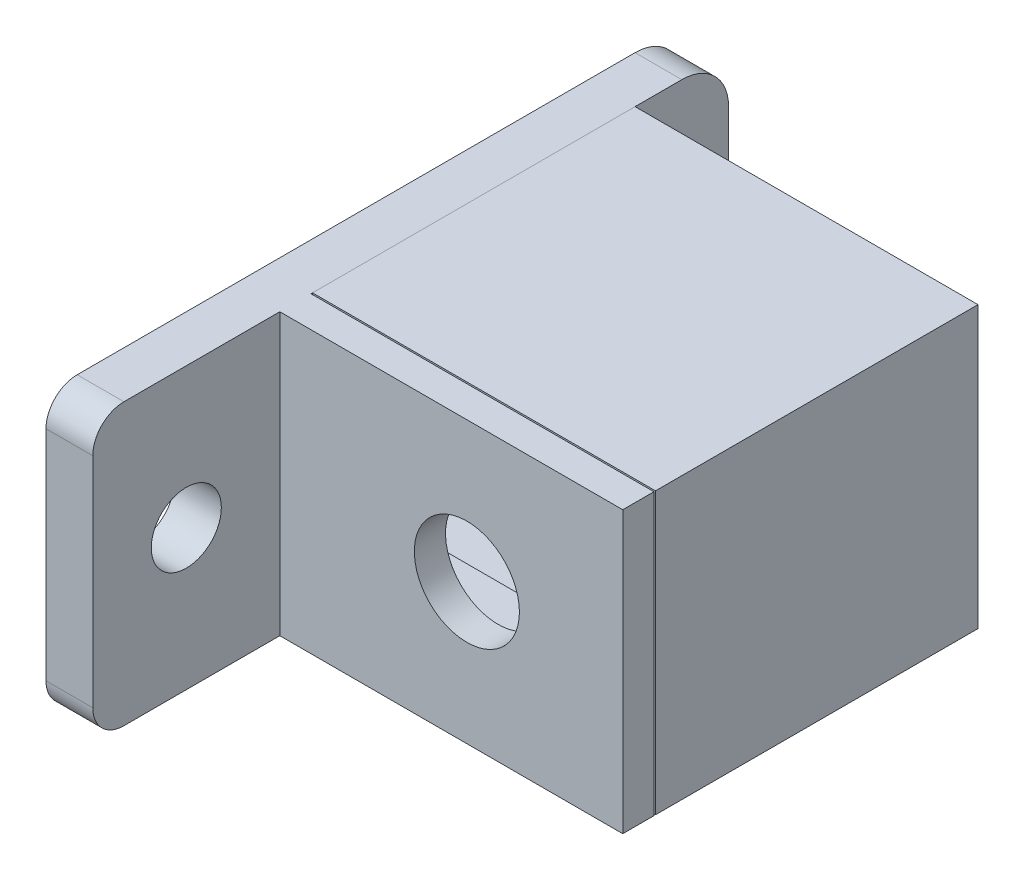
SolidWorks part; units mm, degrees
ref_plane "Front Plane" through (0, 0, 0) normal (0, 0, 1) x (1, 0, 0)
ref_plane "Top Plane" through (0, 0, 0) normal (0, 1, 0) x (1, 0, 0)
ref_plane "Right Plane" through (0, 0, 0) normal (1, 0, 0) x (0, 0, -1)
sketch "Sketch1" plane through (0, 0, 0) normal (1, 0, 0) x (0, 0, -1)
  line L1 (-13.46, 9) -> (-11.46, 9)
  line L2 (-13.46, 9) -> (-13.46, -9)
  line L3 (-13.46, -9) -> (-11.46, -9)
  line L4 (-11.46, 9) -> (-11.46, -9)
  line L5 (0, 0) -> (-11.46, 0) construction
  line L6 (-13.46, -6) -> (-13.46, 6) construction
  line L7 (-13.46, -6) -> (-13.46, 6) construction
  line L8 (4.33, 1.135) -> (4.33, -1.135) construction
  line L9 (4.33, 1.135) -> (4.33, -1.135) construction
  dimension "D1" = 3
  dimension "D2" = 2
extrude "Boss-Extrude1" add sketch "Sketch1" along normal blind 10 and the other way blind 15
sketch "Sketch2" plane through (0, 0, 11.46) normal (0, 0, -1) x (-1, 0, 0)
  line L0 (15, -9) -> (15, 9) construction
  line L1 (15, 9) -> (12, 9)
  line L2 (15, 9) -> (15, -9)
  line L3 (15, -9) -> (12, -9)
  line L4 (12, 9) -> (12, -9)
  line L5 (15, -9) -> (-10, -9) construction
  dimension "D1" = 3
extrude "Boss-Extrude2" add sketch "Sketch2" along normal offset from surface (20.79 mm away) 5
sketch "Sketch3" plane through (-12, 0, 0) normal (1, 0, 0) x (0, 0, -1)
  line L0 (-11.36, 9) -> (-11.36, 7)
  line L1 (-11.46, 9) -> (-11.46, -9) construction
  line L2 (-11.36, 7) -> (7.33, 7)
  line L3 (7.33, 7) -> (7.33, -7)
  line L4 (9.33, -9) -> (9.33, 9)
  line L5 (9.33, 9) -> (-11.46, 9)
  line L6 (-11.46, 9) -> (-11.46, -9)
  line L7 (-11.46, -9) -> (9.33, -9)
  line L8 (9.33, -9) -> (9.33, 9)
  line L9 (9.33, 9) -> (-11.36, 9)
  line L11 (-11.36, -9) -> (9.33, -9)
  line L12 (7.33, -7) -> (-11.36, -7)
  line L13 (-11.36, -7) -> (-11.36, -9)
  line L14 (7.33, 7) -> (9.33, 7) construction
  dimension "D2" = 0.1
  dimension "D3" = 2
  dimension "D1" = 0
extrude "Boss-Extrude3" add sketch "Sketch3" along normal up to surface (22 mm away) separate body up to face at (10, 0, 12.46)
sketch "Sketch4" plane through (-12, 0, 0) normal (1, 0, 0) x (0, 0, -1)
  line L0 (-11.46, 6.5) -> (-9.46, 6.5)
  line L1 (-11.46, -9) -> (-11.46, 9) construction
  line L2 (-9.46, 6.5) -> (-7.96, 8)
  line L3 (-7.96, 8) -> (-7.96, 4.5)
  line L4 (-7.96, 4.5) -> (-11.46, 4.5)
  line L5 (-11.46, 4.5) -> (-11.46, 6.5)
  line L6 (-11.46, 9) -> (-13.46, 9) construction
  line L7 (0, 0) -> (-5.1966, 0) construction
  line L8 (-7.96, -4.5) -> (-11.46, -4.5)
  line L9 (-7.96, -8) -> (-7.96, -4.5)
  line L10 (-9.46, -6.5) -> (-7.96, -8)
  line L11 (-11.46, -6.5) -> (-9.46, -6.5)
  line L12 (-11.46, -4.5) -> (-11.46, -6.5)
  dimension "D1" = 2
  dimension "D2" = 1.5
  dimension "D3" = 3.5
  dimension "D4" = 45
  dimension "D5" = 1
sketch "Sketch5" plane through (-12, 0, 0) normal (1, 0, 0) x (0, 0, -1)
  line L0 (-9.1014, 7) -> (-7.86, 8.2414)
  line L9 (-11.36, 7) -> (7.33, 7) construction
  line L10 (-7.86, 8.2414) -> (-7.86, 7)
  line L11 (-7.86, 7) -> (-9.1014, 7)
  line L12 (-11.36, 7) -> (-11.46, 7) construction
  line L13 (-11.36, 9) -> (-11.36, 7) construction
  line L14 (-11.46, -9) -> (-11.46, 9) construction
  line L15 (-7.96, 8) -> (-7.86, 8) construction
  line L16 (-9.46, 6.5) -> (-7.96, 8) construction
  line L17 (-7.96, 8) -> (-8.0307, 8.0707) construction
  line L18 (0, 0) -> (-5.0644, 0) construction
  line L19 (-7.86, -8.2414) -> (-7.86, -7)
  line L20 (-9.1014, -7) -> (-7.86, -8.2414)
  line L21 (-7.86, -7) -> (-9.1014, -7)
sketch "Sketch6" plane through (10, 0, 0) normal (1, 0, 0) x (0, 0, -1)
  line L1 (9.33, 9) -> (-11.36, 9)
  line L2 (9.33, 9) -> (9.33, -9)
  line L3 (9.33, -9) -> (-11.36, -9)
  line L4 (-11.36, 9) -> (-11.36, -9)
extrude "Boss-Extrude4" add sketch "Sketch6" against normal blind 3
extrude "Cut-Extrude1" cut sketch "Sketch5" along normal up to surface (19 mm away) up to face at (7, 0, 2.015)
extrude "Boss-Extrude5" add sketch "Sketch4" along normal offset from surface (18.5 mm away) 0.5 up to face at (7, 0, 5.7703)
sketch "Sketch7" plane through (0, 0, -9.33) normal (0, 0, -1) x (-1, 0, 0)
  line L0 (12, 9) -> (12, -9) construction
  circle A0 centre (12, 0) radius 3.75
  dimension "D1" = 7.5
extrude "Cut-Extrude2" cut sketch "Sketch7" against normal through all
sketch "Sketch8" plane through (0, 0, 13.46) normal (0, 0, 1) x (1, 0, 0)
  circle A0 centre (0, 0) radius 2.87 construction
  circle A1 centre (0, 0) radius 2.87 construction
  circle A2 centre (0, 0) radius 3.37
  dimension "D1" = 0.5
extrude "Cut-Extrude3" cut sketch "Sketch8" against normal through all
sketch "Sketch9" plane through (-15, 0, 0) normal (-1, 0, 0) x (0, 0, 1)
  line L0 (-9.33, -9) -> (-12.33, -9)
  line L1 (-9.33, -9) -> (-9.33, 9) construction
  line L2 (-15.33, -6) -> (-15.33, 6)
  line L3 (-12.33, 9) -> (-9.33, 9)
  line L4 (-9.33, 9) -> (-9.33, -9)
  line L5 (-15.33, 6) -> (-9.33, 6) construction
  arc A0 (-12.33, -9) -> (-15.33, -6) centre (-12.33, -6) cw
  arc A1 (-15.33, 6) -> (-12.33, 9) centre (-12.33, 6) cw
  dimension "D1" = 6
extrude "Boss-Extrude6" add sketch "Sketch9" against normal up to surface (3 mm away) up to face at (-12, 0, 7.2043)
sketch "Sketch13" plane through (-15, 0, 0) normal (-1, 0, 0) x (0, 0, 1)
  line L1 (-12.33, 6) -> (-9.33, 6)
  line L2 (-12.33, 6) -> (-12.33, -6)
  line L3 (-12.33, -6) -> (-9.33, -6)
  line L4 (-9.33, 6) -> (-9.33, -6)
  arc A0 (-12.33, 9) -> (-15.33, 6) centre (-12.33, 6) ccw construction
  arc A1 (-15.33, -6) -> (-12.33, -9) centre (-12.33, -6) ccw construction
  dimension "D1" = 3
extrude "Boss-Extrude7" add sketch "Sketch13" along normal blind 3
sketch "Sketch14" plane through (-15, 0, 0) normal (-1, 0, 0) x (0, 0, 1)
  line L0 (13.46, -9) -> (13.46, 9)
  line L1 (13.46, 9) -> (23.46, 9)
  line L2 (25.46, 7) -> (25.46, -7)
  line L3 (23.46, -9) -> (13.46, -9)
  line L4 (25.46, 7) -> (13.46, 7) construction
  arc A0 (23.46, 9) -> (25.46, 7) centre (23.46, 7) cw
  arc A1 (25.46, -7) -> (23.46, -9) centre (23.46, -7) cw
  dimension "D1" = 12
  dimension "D2" = 2
extrude "Boss-Extrude8" add sketch "Sketch14" against normal up to surface (3 mm away) up to face at (-12, 0, 3.9348)
hole_wizard "#8 Clearance Hole1" positions "Sketch16" profile "Sketch17" hole size "#8" standard "ANSI Inch" end condition through all
sketch "Sketch16" plane through (-12, 0, 0) normal (1, 0, 0) x (0, 0, -1)
  line L0 (-13.46, 0) -> (-25.46, 0) construction
  line L1 (-13.46, -9) -> (-13.46, 9) construction
  line L2 (-25.46, 7) -> (-25.46, -7) construction
  point P0 (-19.46, 0)
sketch "Sketch17" plane through (-12, 0, 19.46) normal (0, 1, 0) x (0, 0, -1)
  line L0 (0, 0) -> (0, 6)
  line L1 (0, 6) -> (2.2479, 6)
  line L2 (2.2479, 6) -> (2.2479, 0)
  line L5 (2.2479, 0) -> (0, 0)
  line L11 (0, -6.35) -> (0, 107.95) construction
  dimension "Thru Hole Dia." = 4.4958
  dimension "Thru Hole Depth" = 6
